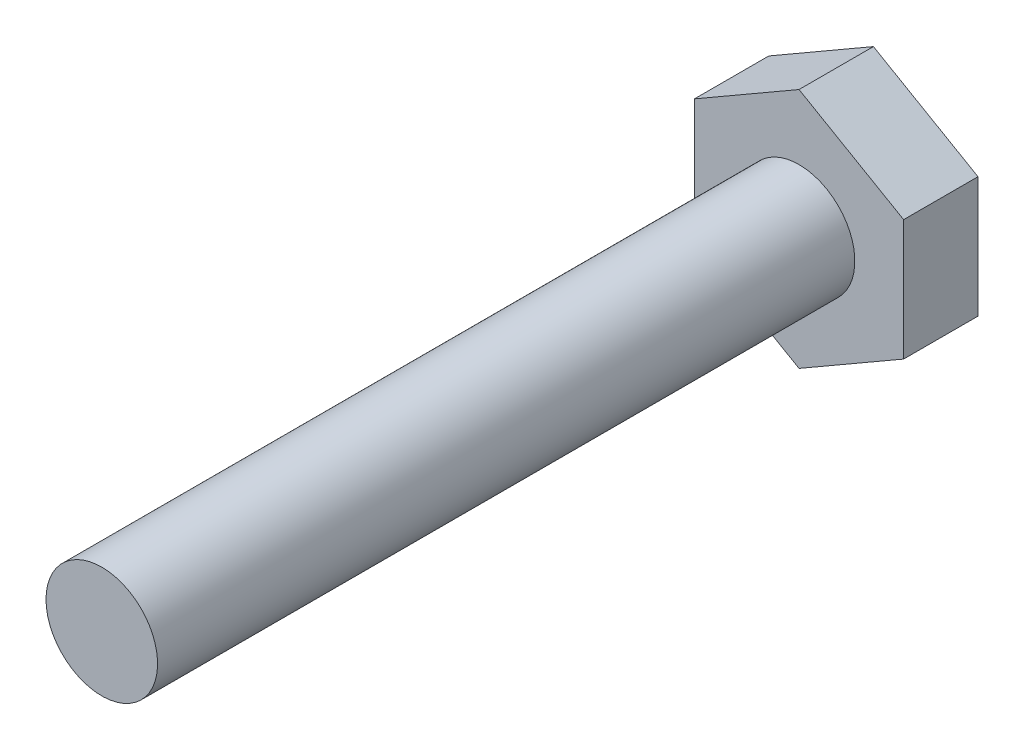
SolidWorks part; units mm, degrees
material "AISI 316 Annealed Stainless Steel Bar (SS)"
ref_plane "Front Plane" through (0, 0, 0) normal (0, 0, 1) x (1, 0, 0)
ref_plane "Top Plane" through (0, 0, 0) normal (0, 1, 0) x (1, 0, 0)
ref_plane "Right Plane" through (0, 0, 0) normal (1, 0, 0) x (0, 0, -1)
sketch "Sketch1" plane through (0, 0, 0) normal (0, 0, 1) x (1, 0, 0)
  line L0 (-5.715, 3.2996) -> (-5.715, -3.2996)
  line L1 (5.715, 3.2996) -> (5.715, -3.2996)
  line L2 (-5.715, 3.2996) -> (0, 6.5991)
  line L3 (0, 6.5991) -> (5.715, 3.2996)
  line L4 (-5.715, -3.2996) -> (0, -6.5991)
  line L5 (0, -6.5991) -> (5.715, -3.2996)
  point P4 (5.715, 0)
  point P7 (-5.715, 0)
  dimension "D1" = 11.43
  dimension "D2" = 11.43
extrude "Boss-Extrude1" add sketch "Sketch1" along normal blind 4.064
sketch "Sketch2" plane through (0, 0, 4.064) normal (0, 0, 1) x (1, 0, 0)
  circle A0 centre (0, 0) radius 3.048
  dimension "D1" = 6.096
extrude "Boss-Extrude2" add sketch "Sketch2" along normal blind 38.1
